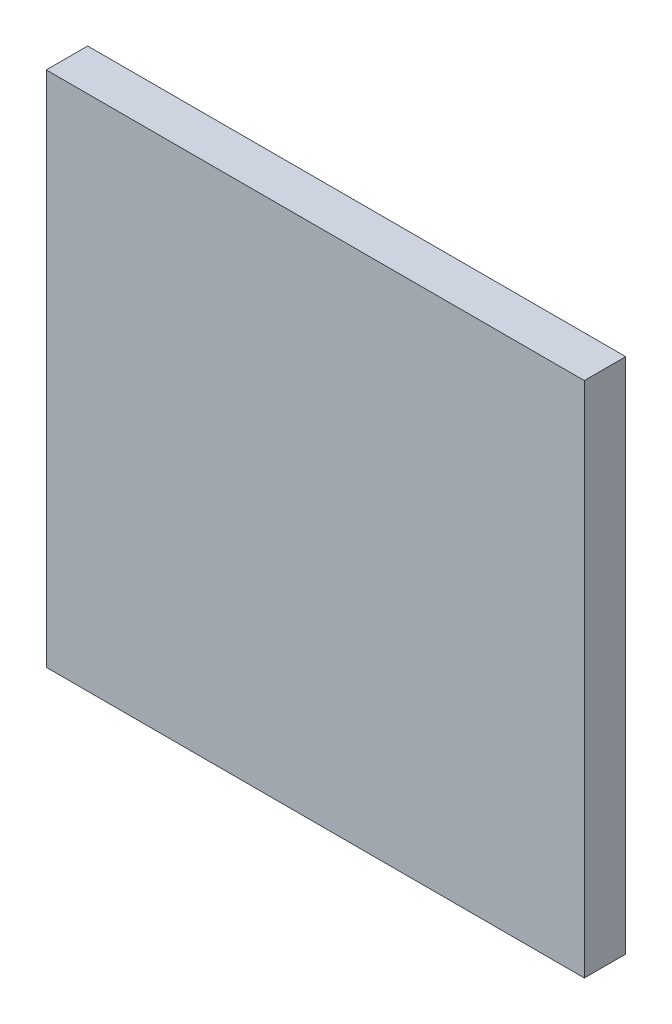
SolidWorks part; units mm, degrees
ref_plane "Alzado" through (0, 0, 0) normal (0, 0, 1) x (1, 0, 0)
ref_plane "Planta" through (0, 0, 0) normal (0, 1, 0) x (1, 0, 0)
ref_plane "Vista lateral" through (0, 0, 0) normal (1, 0, 0) x (0, 0, -1)
sketch "Croquis1" plane through (0, 0, 0) normal (0, 0, 1) x (1, 0, 0)
  line L1 (0, 0) -> (52, 0)
  line L2 (0, 0) -> (0, -50)
  line L3 (0, -50) -> (52, -50)
  line L4 (52, 0) -> (52, -50)
  dimension "D1" = 52
  dimension "D2" = 50
extrude "Saliente-Extruir1" add sketch "Croquis1" along normal blind 4
